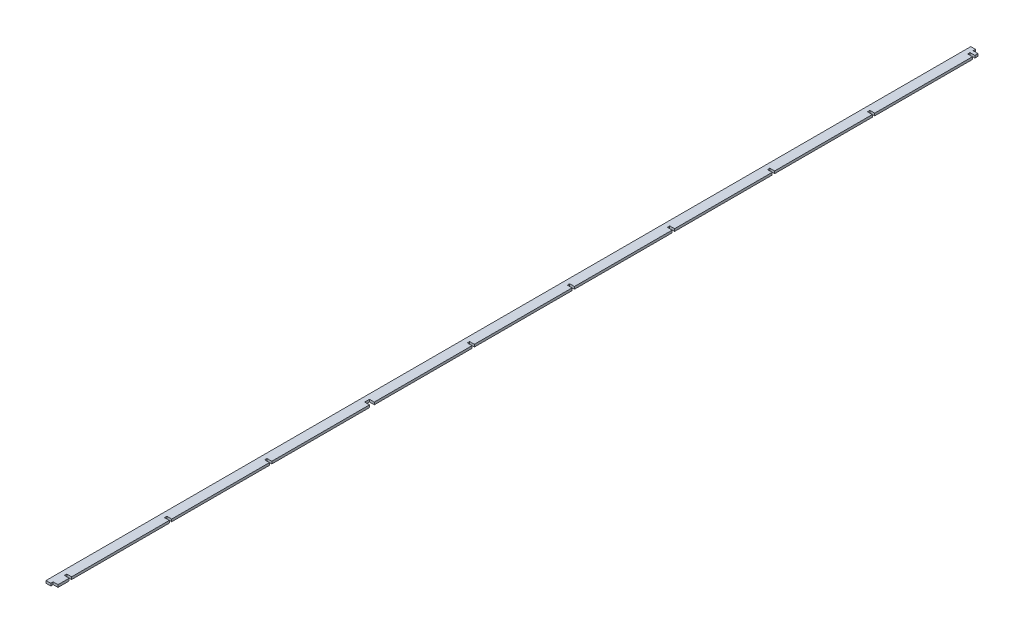
SolidWorks part; units mm, degrees
material "轻木"
ref_plane "前视基准面" through (0, 0, 0) normal (0, 0, 1) x (1, 0, 0)
ref_plane "上视基准面" through (0, 0, 0) normal (0, 1, 0) x (1, 0, 0)
ref_plane "右视基准面" through (0, 0, 0) normal (1, 0, 0) x (0, 0, -1)
other "Configuration Table"
sketch "草图1" plane through (0, 0, 0) normal (0, 0, 1) x (1, 0, 0)
  line L0 (-137.1255, -1006.8019) -> (-137.1255, 48993.1981) construction
  line L1 (-136.0466, -5.3019) -> (-131.1255, -5.3019) construction
  line L2 (-137.1255, -5.3019) -> (-125.1255, -5.3019)
  line L3 (-137.1255, -5.3019) -> (-137.1255, -8.3019)
  line L4 (-137.1255, -8.3019) -> (-125.1255, -8.3019)
  line L5 (-125.1255, -5.3019) -> (-125.1255, -8.3019)
  dimension "D1" = 12
  dimension "D2" = 3
extrude "凸台-拉伸1" add sketch "草图1" along normal blind 1155
sketch "草图3" plane through (0, -5.3019, 0) normal (0, 1, 0) x (1, 0, 0)
  line L0 (-125.1255, -1155) -> (-125.1255, 0) construction
  line L1 (-125.1255, 0) -> (-131.1255, 0)
  line L2 (-125.1255, 0) -> (-125.1255, -3.01)
  line L3 (-125.1255, -3.01) -> (-131.1255, -3.01)
  line L4 (-131.1255, 0) -> (-131.1255, -3.01)
  line L9 (-125.1255, -135) -> (-131.1255, -135)
  line L34 (-125.1255, -10) -> (-131.1255, -10)
  line L35 (-125.1255, -760) -> (-125.1255, -757)
  line L52 (-131.1255, -763) -> (-125.1255, -763)
  line L59 (-131.1255, -763) -> (-131.1255, -760)
  line L60 (-125.1255, -135) -> (-125.1255, -132)
  line L63 (-131.1255, -760) -> (-125.1255, -760)
  line L65 (-125.1255, -10) -> (-125.1255, -7)
  line L66 (-125.1255, -7) -> (-131.1255, -7)
  line L67 (-131.1255, -10) -> (-131.1255, -7)
  line L68 (-125.1255, -132) -> (-131.1255, -132)
  line L69 (-131.1255, -135) -> (-131.1255, -132)
  line L70 (-125.1255, -260) -> (-131.1255, -260)
  line L71 (-125.1255, -260) -> (-125.1255, -257)
  line L72 (-125.1255, -257) -> (-131.1255, -257)
  line L73 (-131.1255, -260) -> (-131.1255, -257)
  line L74 (-125.1255, -385) -> (-131.1255, -385)
  line L75 (-125.1255, -385) -> (-125.1255, -382)
  line L76 (-125.1255, -382) -> (-131.1255, -382)
  line L77 (-131.1255, -385) -> (-131.1255, -382)
  line L78 (-125.1255, -510) -> (-131.1255, -510)
  line L79 (-125.1255, -510) -> (-125.1255, -507)
  line L80 (-125.1255, -507) -> (-131.1255, -507)
  line L81 (-131.1255, -510) -> (-131.1255, -507)
  line L82 (-125.1255, -635) -> (-131.1255, -635)
  line L83 (-125.1255, -635) -> (-125.1255, -632)
  line L84 (-125.1255, -632) -> (-131.1255, -632)
  line L85 (-131.1255, -635) -> (-131.1255, -632)
  line L86 (-125.1255, -10) -> (-125.1255, -135) construction
  line L87 (-125.1255, -763) -> (-125.1255, -760)
  line L88 (-125.1255, -757) -> (-131.1255, -757)
  line L89 (-131.1255, -757) -> (-131.1255, -760)
  line L90 (-131.1255, -885) -> (-125.1255, -885)
  line L91 (-131.1255, -888) -> (-131.1255, -885)
  line L92 (-131.1255, -888) -> (-125.1255, -888)
  line L93 (-125.1255, -888) -> (-125.1255, -885)
  line L94 (-131.1255, -1010) -> (-125.1255, -1010)
  line L95 (-131.1255, -1013) -> (-131.1255, -1010)
  line L96 (-131.1255, -1013) -> (-125.1255, -1013)
  line L97 (-125.1255, -1013) -> (-125.1255, -1010)
  line L98 (-131.1255, -760) -> (-131.1255, -885) construction
  line L99 (-131.1255, -1135) -> (-125.1255, -1135)
  line L100 (-131.1255, -1138) -> (-131.1255, -1135)
  line L101 (-131.1255, -1138) -> (-125.1255, -1138)
  line L102 (-125.1255, -1138) -> (-125.1255, -1135)
  line L104 (-131.1255, -1155) -> (-125.1255, -1155)
  line L105 (-131.1255, -1155) -> (-131.1255, -1152)
  line L106 (-131.1255, -1152) -> (-125.1255, -1152)
  line L107 (-125.1255, -1155) -> (-125.1255, -1152)
  line M3 (-125.1255, 0) -> (-137.1255, 0)
  line M6 (-125.1255, -1155) -> (-125.1255, 0)
  dimension "D1" = 125
  dimension "D3" = 4
  dimension "D2" = 125
  dimension "D5" = 7
  dimension "D6" = 3
  dimension "D7" = 125
  dimension "D8" = 6
  dimension "D9" = 3
  dimension "D10" = 3
  dimension "D11" = 17
  dimension "D12" = 6
  dimension "D13" = 3
  dimension "D4" = 6
extrude "切除-拉伸1" cut sketch "草图3" against normal through all contours L4 L3 M3 M6 | L67 L34 L66 M6 | L69 L9 L68 M6 | L73 L70 L72 M6 | L77 L74 L76 M6 | L81 L78 L80 M6 | L85 L82 L84 M6 | L88 L89 L63 M6 | L63 L59 L52 M6 | L91 L92 L90 M6 | L95 L96 L94 M6 | L100 L101 L99 M6 | L106 L105 L104 M6
